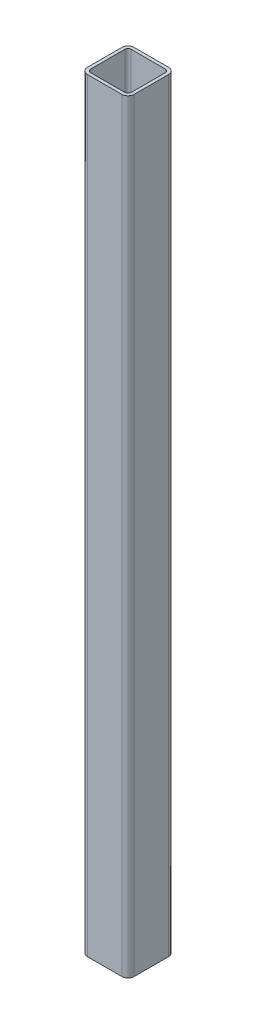
SolidWorks part; units mm, degrees
ref_plane "前视基准面" through (0, 0, 0) normal (0, 0, 1) x (1, 0, 0)
ref_plane "上视基准面" through (0, 0, 0) normal (0, 1, 0) x (1, 0, 0)
ref_plane "右视基准面" through (0, 0, 0) normal (1, 0, 0) x (0, 0, -1)
sketch "草图1" plane through (0, 0, 0) normal (0, 1, 0) x (1, 0, 0)
  line L0 (-11, -13) -> (11, -13)
  line L1 (-11, -15) -> (11, -15)
  line L2 (-15, -11) -> (-15, 11)
  line L3 (-11, 15) -> (11, 15)
  line L4 (15, -11) -> (15, 11)
  line L5 (13, -11) -> (13, 11)
  line L6 (-11, 13) -> (11, 13)
  line L7 (-13, -11) -> (-13, 11)
  arc A0 (-11, -15) -> (-15, -11) centre (-11, -11) cw
  arc A1 (11, -15) -> (15, -11) centre (11, -11) ccw
  arc A2 (11, 15) -> (15, 11) centre (11, 11) cw
  arc A3 (-15, 11) -> (-11, 15) centre (-11, 11) cw
  arc A4 (11, -13) -> (13, -11) centre (11, -11) ccw
  arc A5 (11, 13) -> (13, 11) centre (11, 11) cw
  arc A6 (-13, 11) -> (-11, 13) centre (-11, 11) cw
  arc A7 (-11, -13) -> (-13, -11) centre (-11, -11) cw
extrude "凸台-拉伸1" add sketch "草图1" along normal mid plane 490
